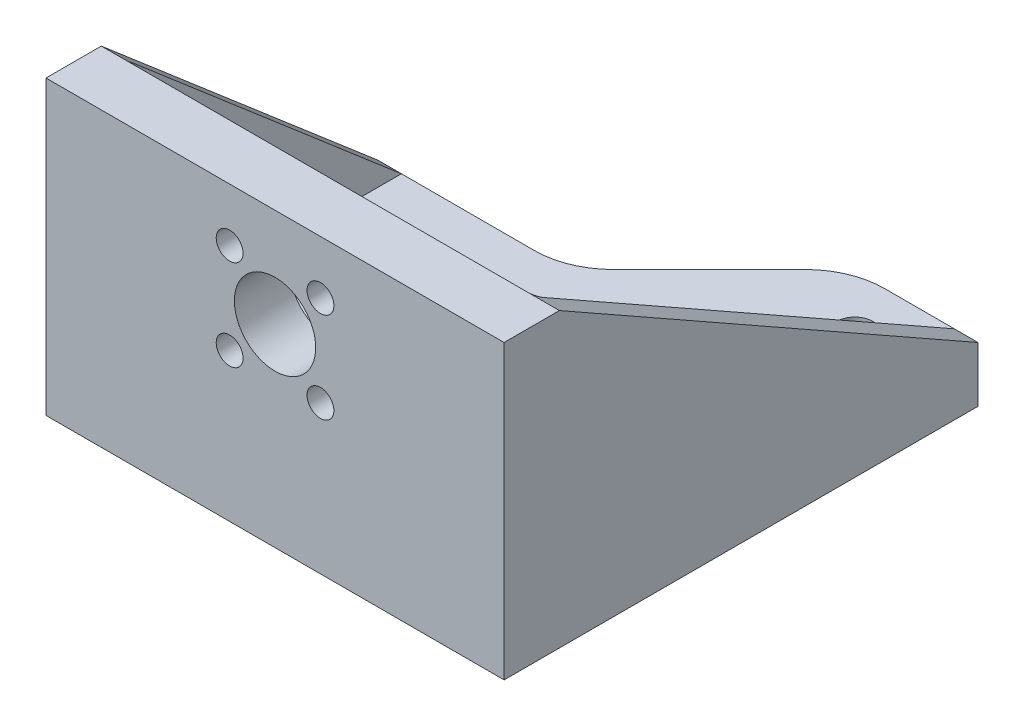
SolidWorks part; units mm, degrees
material "ABS"
ref_plane "Front Plane" through (0, 0, 0) normal (0, 0, 1) x (1, 0, 0)
ref_plane "Top Plane" through (0, 0, 0) normal (0, 1, 0) x (1, 0, 0)
ref_plane "Right Plane" through (0, 0, 0) normal (1, 0, 0) x (0, 0, -1)
sketch "Sketch1" plane through (0, 0, 0) normal (0, 1, 0) x (1, 0, 0)
  line L1 (0, 0) -> (58, 0)
  line L2 (0, 0) -> (0, 60)
  line L3 (0, 60) -> (58, 60)
  line L4 (58, 0) -> (58, 60)
  dimension "D1" = 60
  dimension "D2" = 58
extrude "Boss-Extrude1" add sketch "Sketch1" along normal blind 7
sketch "Sketch2" plane through (0, 7, 0) normal (0, 1, 0) x (1, 0, 0)
  line L0 (0, 60) -> (0, 0) construction
  line L1 (0, 7) -> (58, 7)
  line L2 (0, 7) -> (0, 0)
  line L3 (0, 0) -> (58, 0)
  line L4 (58, 7) -> (58, 0)
  dimension "D1" = 7
extrude "Boss-Extrude2" add sketch "Sketch2" along normal blind 30
hole_wizard "M4 Clearance Slot3" [suppressed] positions "Sketch3" profile "Sketch4" size "M4" standard "ANSI Metric"
sketch "Sketch3" plane through (0, 7, 0) normal (0, 1, 0) x (1, 0, 0)
  line L0 (32.05, 70) -> (32.05, 7) construction
  line L1 (64.1, 70) -> (0, 70) construction
  line L2 (64.1, 7) -> (0, 7) construction
  line L4 (16.235, 62.5) -> (47.865, 62.5) construction
  line L5 (47.865, 62.5) -> (47.865, 14.5) construction
  line L6 (47.865, 14.5) -> (16.235, 14.5) construction
  line L7 (16.235, 14.5) -> (16.235, 62.5) construction
  line L9 (0, 38.5) -> (16.235, 38.5) construction
  line L10 (0, 70) -> (0, 7) construction
  line L12 (40.365, 62.5) -> (55.365, 62.5) construction
  point P2 (47.865, 62.5)
  point P4 (47.865, 14.5)
  point P26 (32.05, 62.5)
  dimension "D1" = 31.63
  dimension "D2" = 48
  dimension "D4" = 15
sketch "Sketch4" plane through (47.865, 7, -62.5) normal (1, 0, 0) x (0, 0, 1)
  line L0 (0, 0) -> (0, 7)
  line L1 (0, 7) -> (2.25, 7)
  line L2 (2.25, 7) -> (2.25, 0)
  line L5 (2.25, 0) -> (0, 0)
  line L11 (0, -6.35) -> (0, 107.95) construction
  dimension "Thru Hole Dia." = 4.5
  dimension "Thru Hole Depth" = 7
sketch "Sketch5" plane through (0, 0, -7) normal (0, 0, -1) x (-1, 0, 0)
  line L0 (0, 24.5) -> (-58, 24.5) construction
  line L1 (0, 37) -> (0, 7) construction
  line L2 (-58, 37) -> (-58, 7) construction
  line L3 (-29, 24.5) -> (-29, 7) construction
  line L4 (-58, 7) -> (0, 7) construction
  circle A0 centre (-29, 24.5) radius 5.15
  dimension "D1" = 10.3
  dimension "D2" = 17.5
extrude "Cut-Extrude1" cut sketch "Sketch5" against normal through all
hole_wizard "M3 Clearance Hole1" positions "Sketch6" profile "Sketch7" hole size "M3" standard "ANSI Metric" end condition through all
sketch "Sketch6" plane through (0, 0, -7) normal (0, 0, -1) x (-1, 0, 0)
  line L2 (-23.25, 18.75) -> (-34.75, 18.75) construction
  line L3 (-23.25, 18.75) -> (-23.25, 30.25)
  line L4 (-23.25, 30.25) -> (-34.75, 30.25)
  line L5 (-34.75, 18.75) -> (-34.75, 30.25)
  circle A1 centre (-29, 24.5) radius 5.15 construction
  circle A2 centre (-29, 24.5) radius 5.15 construction
  point P0 (-34.75, 18.75)
  point P2 (-23.25, 18.75)
  point P130 (-23.25, 30.25)
  point P133 (-34.75, 30.25)
  point P139 (-29, 18.75)
  point P140 (-23.25, 24.5)
  dimension "D1" = 11.5
  dimension "D2" = 11.5
sketch "Sketch7" plane through (34.75, 18.75, -7) normal (1, 0, 0) x (0, 1, 0)
  line L0 (0, 0) -> (0, 7)
  line L1 (0, 7) -> (1.7, 7)
  line L2 (1.7, 7) -> (1.7, 0)
  line L5 (1.7, 0) -> (0, 0)
  line L11 (0, -6.35) -> (0, 107.95) construction
  dimension "Thru Hole Dia." = 3.4
  dimension "Thru Hole Depth" = 7
hole_wizard "M2 Clearance Hole1" [suppressed] positions "Sketch8" profile "Sketch9" hole size "M2" standard "ANSI Metric"
sketch "Sketch8" plane through (0, 0, 0) normal (-1, 0, 0) x (0, 0, 1)
  line L0 (-38.5, 7) -> (-38.5, 0) construction
  line L1 (-70, 7) -> (-7, 7) construction
  line L2 (-70, 0) -> (0, 0) construction
  line L4 (-29.5, 3.5) -> (-47.5, 3.5) construction
  point P0 (-47.5, 3.5)
  point P2 (-29.5, 3.5)
  point P16 (-38.5, 3.5)
  dimension "D1" = 18
sketch "Sketch9" plane through (0, 3.5, -47.5) normal (0, 1, 0) x (0, 0, 1)
  line L0 (0, 0) -> (0, 35.721)
  line L1 (0, 35.721) -> (1.2, 35)
  line L2 (1.2, 35) -> (1.2, 0)
  line L5 (1.2, 0) -> (0, 0)
  line L10 (0, 35.721) -> (-1.2, 35) construction
  line L11 (0, -6.35) -> (0, 107.95) construction
  dimension "Hole Dia." = 2.4
  dimension "Hole Depth" = 35
  dimension "Drill Angle" = 118
sketch "Sketch11" plane through (0, 7, 0) normal (0, 1, 0) x (1, 0, 0)
  line L0 (0, 48) -> (28, 48)
  line L1 (0, 60) -> (0, 7) construction
  line L2 (28, 48) -> (40, 60)
  line L3 (58, 60) -> (0, 60) construction
  line L4 (0, 48) -> (0, 60)
  line L5 (0, 60) -> (40, 60)
  dimension "D1" = 135
  dimension "D2" = 12
  dimension "D3" = 40
extrude "Cut-Extrude2" [suppressed] cut sketch "Sketch11" against normal through all
sketch "Sketch12" [suppressed] plane through (0, 7, 0) normal (0, 1, 0) x (1, 0, 0)
  line L0 (18.475, 48) -> (18.475, 11.5)
  line L1 (0, 48) -> (28, 48) construction
  line L2 (18.475, 11.5) -> (0, 11.5)
  line L3 (0, 48) -> (0, 7) construction
  line L4 (0, 10.5) -> (19.475, 10.5)
  line L5 (19.475, 10.5) -> (19.475, 48)
  line L6 (19.475, 48) -> (18.475, 48)
  line L7 (0, 10.5) -> (0, 11.5)
  dimension "D3" = 18.475
  dimension "D1" = 1
  dimension "D2" = 1
  dimension "D4" = 36.5
extrude "Cut-Extrude3" [suppressed] cut sketch "Sketch12" against normal through all
sketch "Sketch13" [suppressed] plane through (0, 7, 0) normal (0, 1, 0) x (1, 0, 0)
  line L0 (19.475, 58) -> (28, 58) construction
  line L1 (24.475, 51.25) -> (27.975, 51.25)
  line L2 (24.475, 51.25) -> (24.475, 25)
  line L3 (24.475, 25) -> (27.975, 25)
  line L4 (27.975, 51.25) -> (27.975, 25)
  line L5 (19.475, 20.5) -> (19.475, 58) construction
  dimension "D1" = 3.5
  dimension "D2" = 26.25
  dimension "D3" = 5
  dimension "D4" = 6.75
extrude "Cut-Extrude4" [suppressed] cut sketch "Sketch13" against normal through all
sketch "Sketch16" [suppressed] plane through (0, 7, 0) normal (0, 1, 0) x (1, 0, 0)
  line L0 (19.475, 58) -> (36.975, 58)
  line L1 (36.975, 58) -> (36.975, 20.5)
  line L3 (19.475, 20.5) -> (19.475, 58)
  line L4 (24.475, 51.25) -> (27.975, 51.25)
  line L5 (27.975, 51.25) -> (27.975, 25)
  line L6 (27.975, 25) -> (24.475, 25)
  line L7 (24.475, 25) -> (24.475, 51.25)
  line L8 (36.975, 20.5) -> (19.475, 20.5)
  dimension "D1" = 17.5
extrude "Boss-Extrude5" [suppressed] add sketch "Sketch16" along normal blind 4
sketch "Sketch14" [suppressed] plane through (0, 0, 0) normal (-1, 0, 0) x (0, 0, 1)
  line L0 (-10.5, 7) -> (-7, 42)
  line L1 (-7, 42) -> (-7, 7)
  line L2 (-7, 7) -> (-10.5, 7)
extrude "Boss-Extrude3" [suppressed] add sketch "Sketch14" against normal blind 3
sketch "Sketch15" plane through (58, 0, 0) normal (1, 0, 0) x (0, 0, -1)
  line L0 (60, 7) -> (7, 37)
  line L1 (7, 37) -> (7, 7)
  line L2 (7, 7) -> (60, 7)
extrude "support" add sketch "Sketch15" against normal blind 3
fillet "Fillet1" [suppressed] radius 10
hole_wizard "M4 Clearance Hole1" [suppressed] positions "Sketch17" profile "Sketch18" hole size "M4" standard "ANSI Metric"
sketch "Sketch17" [suppressed] plane through (19.475, 0, 0) normal (-1, 0, 0) x (0, 0, 1)
  line L0 (-58, 5.5) -> (-20.5, 5.5) construction
  line L1 (-58, 0) -> (-58, 11) construction
  line L2 (-20.5, 0) -> (-20.5, 7) construction
  point P0 (-47.5, 5.5)
  point P2 (-29.5, 5.5)
  dimension "D1" = 10.5
  dimension "D2" = 18
sketch "Sketch18" plane through (19.475, 5.5, -47.5) normal (0, 1, 0) x (0, 0, 1)
  line L0 (0, 0) -> (0, 15.8819)
  line L1 (0, 15.8819) -> (2.25, 14.53)
  line L2 (2.25, 14.53) -> (2.25, 0)
  line L5 (2.25, 0) -> (0, 0)
  line L10 (0, 15.8819) -> (-2.25, 14.53) construction
  line L11 (0, -6.35) -> (0, 107.95) construction
  dimension "Hole Dia." = 4.5
  dimension "Hole Depth" = 14.53
  dimension "Drill Angle" = 118
hole_wizard "M4 Clearance Hole2" positions "Sketch19" profile "Sketch20" hole size "M4" standard "ANSI Metric" end condition through all
sketch "Sketch19" plane through (0, 7, 0) normal (0, 1, 0) x (1, 0, 0)
  line L0 (34.15, 7) -> (23.85, 7) construction
  line L1 (34.15, 7) -> (23.85, 7) construction
  line L2 (29, 7) -> (29, 60) construction
  line L3 (55, 60) -> (0, 60) construction
  line L5 (49, 53.4) -> (49, 13.4) construction
  line L7 (49, 33.4) -> (9, 33.4) construction
  point P0 (49, 53.4)
  point P2 (49, 13.4)
  point P4 (9, 33.4)
  point P25 (29, 33.4)
  dimension "D1" = 40
  dimension "D2" = 40
  dimension "D3" = 6.4
sketch "Sketch20" plane through (49, 7, -53.4) normal (1, 0, 0) x (0, 0, 1)
  line L0 (0, 0) -> (0, 7)
  line L1 (0, 7) -> (2.25, 7)
  line L2 (2.25, 7) -> (2.25, 0)
  line L5 (2.25, 0) -> (0, 0)
  line L11 (0, -6.35) -> (0, 107.95) construction
  dimension "Thru Hole Dia." = 4.5
  dimension "Thru Hole Depth" = 7
sketch "Sketch21" plane through (0, 7, 0) normal (0, 1, 0) x (1, 0, 0)
  line L0 (42, 60) -> (24, 42)
  line L1 (55, 60) -> (0, 60) construction
  line L2 (24, 42) -> (0, 42)
  line L3 (0, 60) -> (0, 7) construction
  line L4 (58, 7) -> (58, 60) construction
  line L5 (0, 42) -> (0, 60)
  line L6 (0, 60) -> (42, 60)
  dimension "D1" = 45
  dimension "D2" = 16
  dimension "D3" = 18
extrude "Cut-Extrude5" cut sketch "Sketch21" against normal through all
sketch "Sketch22" plane through (0, 0, 0) normal (-1, 0, 0) x (0, 0, 1)
  line L0 (-42, 7) -> (-7, 37)
  line L1 (-7, 37) -> (-7, 7)
  line L2 (-7, 7) -> (-42, 7)
extrude "Boss-Extrude6" add sketch "Sketch22" against normal blind 3
fillet "Fillet2" radius 10 2 edges at (42, 3.5, -60) (24, 3.5, -42)
fillet "Fillet3" radius 1 3 edges at (55, 22, -7) (29, 7, -7) (3, 22, -7)
